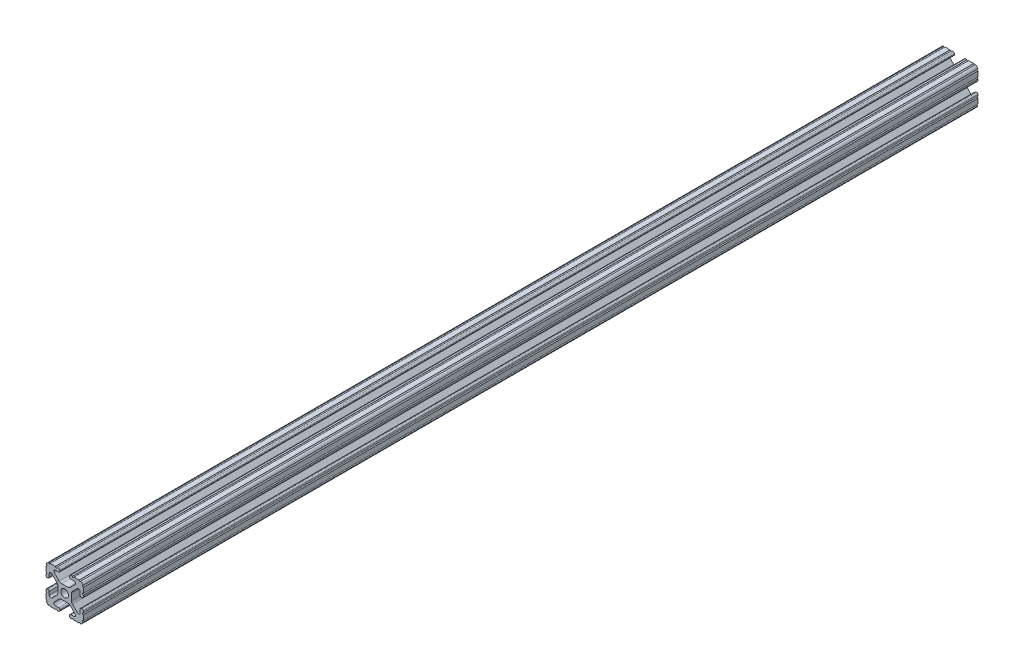
SolidWorks part; units mm, degrees
ref_plane "Front Plane" through (0, 0, 0) normal (0, 0, 1) x (1, 0, 0)
ref_plane "Top Plane" through (0, 0, 0) normal (0, 1, 0) x (1, 0, 0)
ref_plane "Right Plane" through (0, 0, 0) normal (1, 0, 0) x (0, 0, -1)
sketch "Sketch2" plane through (0, 0, 0) normal (0, 0, 1) x (1, 0, 0)
  line L0 (0, 12.7) -> (0, -12.7) construction
  line L1 (-12.7, 0) -> (12.7, 0) construction
  line L2 (3.2512, -12.7) -> (12.7, -12.7)
  line L3 (12.7, -12.7) -> (12.7, -3.2512)
  line L4 (3.2512, -12.7) -> (3.2512, -10.4902)
  line L5 (3.2512, -10.4902) -> (8.9276, -10.4902)
  line L6 (8.9276, -10.4902) -> (3.0856, -4.6482)
  line L7 (0, 0) -> (12.7, -12.7) construction
  line L8 (12.7, -3.2512) -> (10.4902, -3.2512)
  line L9 (10.4902, -3.2512) -> (10.4902, -8.9276)
  line L10 (10.4902, -8.9276) -> (4.6482, -3.0856)
  circle A0 centre (0, 0) radius 2.6035
  arc A1 (6.3485, -10.4902) -> (7.1039, -8.6665) centre (6.3485, -9.4219) ccw construction
  point P8 (0, -4.6482)
  dimension "Center Hole Diameter" = 5.207
  dimension "Rail Height" = 25.4
  dimension "Rail Width" = 25.4
  dimension "T-Slot Width" = 6.5024
  dimension "Slot Inner Width" = 14.8336
  dimension "Thickness" = 2.2098
  dimension "Slot Depth" = 5.842
  dimension "D1" = 2.2098
sketch "Sketch3" plane through (0, 0, 0) normal (1, 0, 0) x (0, 0, -1)
  line L0 (-304.8, -12.7) -> (304.8, -12.7) construction
  line L1 (-279.4, 0) -> (279.4, 0) construction
  dimension "Length" = 609.6
  dimension "D1" = 25.4
sketch "Sketch4" plane through (0, 0, 0) normal (0, 0, 1) x (1, 0, 0)
  line L0 (4.1904, -12.7) -> (10.1173, -12.7)
  line L1 (3.2512, -12.7) -> (12.7, -12.7) construction
  line L2 (3.2512, -12.7) -> (3.2512, -10.4902) construction
  line L3 (3.2512, -10.4902) -> (8.9276, -10.4902) construction
  line L4 (3.2512, -11.4294) -> (3.2512, -11.7608)
  line L5 (4.1904, -10.4902) -> (6.3485, -10.4902)
  line L6 (0, -4.6482) -> (2.164, -4.6482)
  line L7 (8.9276, -10.4902) -> (3.0856, -4.6482) construction
  line L8 (3.7373, -5.2999) -> (7.1039, -8.6665)
  line L9 (12.7, -12.7) -> (12.7, -3.2512) construction
  line L10 (10.4902, -8.9276) -> (4.6482, -3.0856) construction
  line L11 (10.4902, -3.2512) -> (10.4902, -8.9276) construction
  line L12 (10.4902, -6.3485) -> (10.4902, -4.1904)
  line L13 (12.7, -3.2512) -> (10.4902, -3.2512) construction
  line L14 (11.4294, -3.2512) -> (11.7608, -3.2512)
  line L15 (12.7, -4.1904) -> (12.7, -10.1173)
  line L16 (8.6665, -7.1039) -> (5.2999, -3.7373)
  line L17 (4.6482, 0) -> (4.6482, -2.164)
  line L18 (-12.7, 0) -> (12.7, 0) construction
  line L19 (0, -4.6482) -> (0, -2.6035)
  line L20 (0, 12.7) -> (0, -12.7) construction
  line L21 (4.6482, 0) -> (2.6035, 0)
  arc A0 (3.2512, -11.7608) -> (4.1904, -12.7) centre (4.1904, -11.7608) ccw
  arc A2 (3.2512, -11.4294) -> (4.1904, -10.4902) centre (4.1904, -11.4294) cw
  arc A3 (6.3485, -10.4902) -> (7.1039, -8.6665) centre (6.3485, -9.4219) ccw
  arc A4 (2.164, -4.6482) -> (3.7373, -5.2999) centre (2.164, -6.8732) cw
  arc A5 (10.1173, -12.7) -> (12.7, -10.1173) centre (10.1173, -10.1173) ccw
  arc A6 (8.6665, -7.1039) -> (10.4902, -6.3485) centre (9.4219, -6.3485) ccw
  arc A7 (10.4902, -4.1904) -> (11.4294, -3.2512) centre (11.4294, -4.1904) cw
  arc A8 (11.7608, -3.2512) -> (12.7, -4.1904) centre (11.7608, -4.1904) cw
  arc A9 (5.2999, -3.7373) -> (4.6482, -2.164) centre (6.8732, -2.164) cw
  circle A10 centre (0, 0) radius 2.6035 construction
  arc A11 (0, -2.6035) -> (2.6035, 0) centre (0, 0) ccw
  dimension "D1" = 2.5827
  dimension "D2" = 2.225
  dimension "D3" = 0.9392
extrude "Boss-Extrude1" add sketch "Sketch4" along normal mid plane 609.6
sketch "Sketch5" plane through (0, 0, 0) normal (0, 0, 1) x (1, 0, 0)
  line L0 (3.2512, -12.7) -> (12.7, -12.7) construction
  line L1 (4.1904, -10.4902) -> (6.3485, -10.4902) construction
  line L3 (0, 0) -> (12.7, -12.7) construction
  line L4 (6.3485, -10.4902) -> (6.3485, -12.7) construction
  line L5 (8.9276, -10.4902) -> (3.0856, -4.6482) construction
  circle A0 centre (10.3562, -12.7) radius 0.5524
  circle A1 centre (5.796, -12.7) radius 0.5524
  circle A2 centre (12.7, -10.3562) radius 0.5524
  circle A3 centre (12.7, -5.796) radius 0.5524
  point P10 (5.2694, -10.4902)
  point P12 (9.4219, -6.3485)
  dimension "D1" = 1.1049
extrude "Cut-Extrude1" cut sketch "Sketch5" against normal through all both and the other way through all
mirror "Mirror1" about plane through (0, 0, 0) normal (1, 0, 0) of bodies 137 134
mirror "Mirror2" about plane through (0, 0, 0) normal (0, 1, 0) of bodies 135
sketch "Sketch6" plane through (0, 12.7, 0) normal (0, 1, 0) x (1, 0, 0)
  line L0 (-12.58, 304.8) -> (-12.58, -304.8) construction
  line L1 (12.58, 304.8) -> (-12.58, 304.8) construction
  line L2 (12.58, 304.8) -> (12.58, 279.64) construction
  line L3 (12.58, 279.64) -> (-12.58, 279.64) construction
  line L4 (-12.58, 304.8) -> (-12.58, 279.64) construction
  line L5 (0, 304.8) -> (0, 279.64) construction
  line L6 (12.58, 292.22) -> (-12.58, 292.22) construction
  circle A0 centre (0, 292.22) radius 3.2639
  dimension "D1" = 6.5278
extrude "Cut-Extrude2" cut sketch "Sketch6" against normal through all
sketch "Sketch8" plane through (0, 12.7, 0) normal (0, 1, 0) x (1, 0, 0)
  line L0 (0, 292.22) -> (0, 166.1369)
  line L1 (0, 166.1369) -> (0, -138.6631)
  circle A0 centre (0, 166.1369) radius 3.2639
  circle A1 centre (0, -138.6631) radius 3.2639
  circle A2 centre (0, 292.22) radius 3.2639 construction
  point P8 (0, -80.0957)
  point P9 (0, -138.6631)
  dimension "D1" = 304.8
extrude "Cut-Extrude3" cut sketch "Sketch8" against normal through all contours A0 | A1
equation "\"D1@Boss-Extrude1\"=\"Length@Sketch3\""
equation "\"D1@Sketch2\"=\"Thickness@Sketch2\""
equation "\"D2@Sketch4\"=\"Slot Inner Width@Sketch2\"*0.15"
equation "\"D1@Sketch4\"=\"D3@Sketch4\"*2.75"
equation "\"D3@Sketch4\"=\"Thickness@Sketch2\"*0.425"
equation "\"D1@Sketch5\"=\"Thickness@Sketch2\"*0.5"
